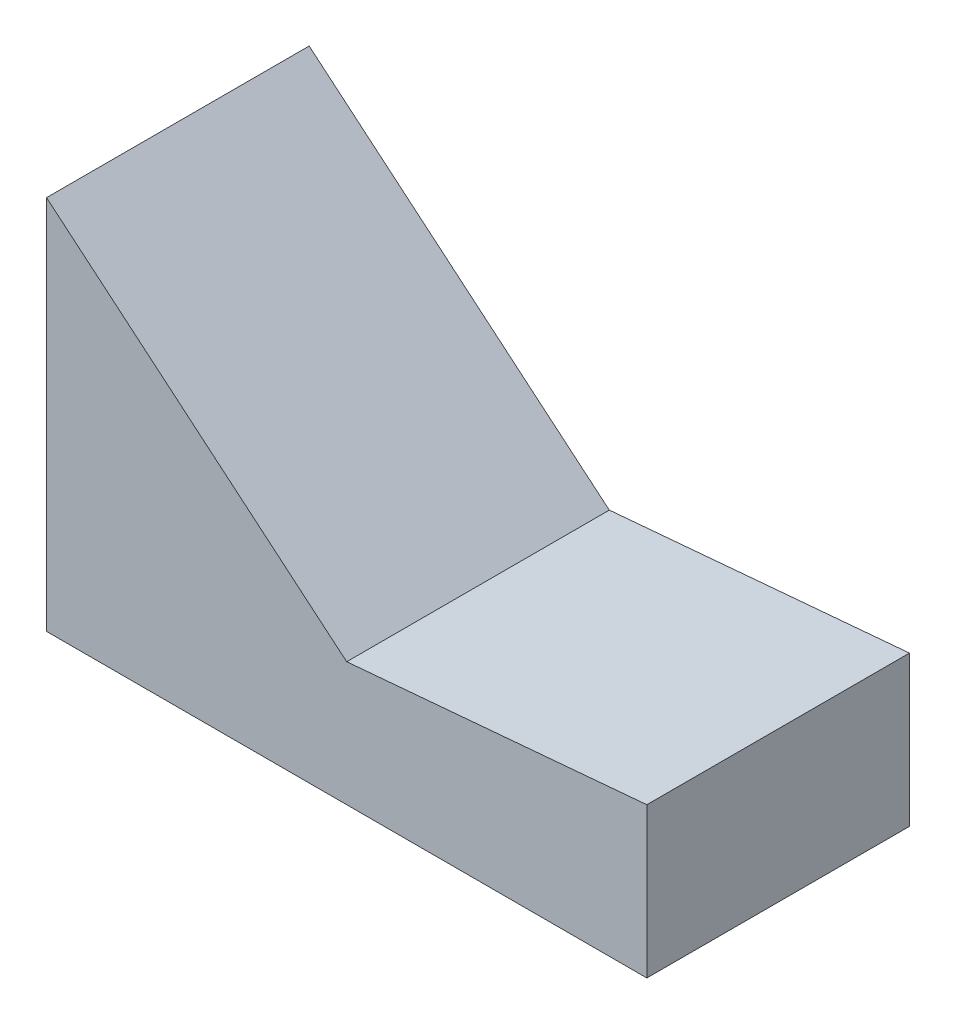
SolidWorks part; units mm, degrees
ref_plane "Plan de face" through (0, 0, 0) normal (0, 0, 1) x (1, 0, 0)
ref_plane "Plan de dessus" through (0, 0, 0) normal (0, 1, 0) x (1, 0, 0)
ref_plane "Plan de droite" through (0, 0, 0) normal (1, 0, 0) x (0, 0, -1)
sketch "Esquisse1" plane through (0, 0, 0) normal (0, 0, 1) x (1, 0, 0)
  line L0 (0, 0) -> (-80, 0)
  line L1 (-80, 0) -> (-80, 50.0644)
  line L2 (-80, 50.0644) -> (-40, 16.5005)
  line L3 (-40, 16.5005) -> (0, 20)
  line L4 (0, 20) -> (0, 0)
  dimension "D1" = 80
  dimension "D2" = 40
  dimension "D3" = 20
  dimension "D4" = 50
  dimension "D5" = 85
extrude "Boss.-Extru.1" add sketch "Esquisse1" along normal blind 35
